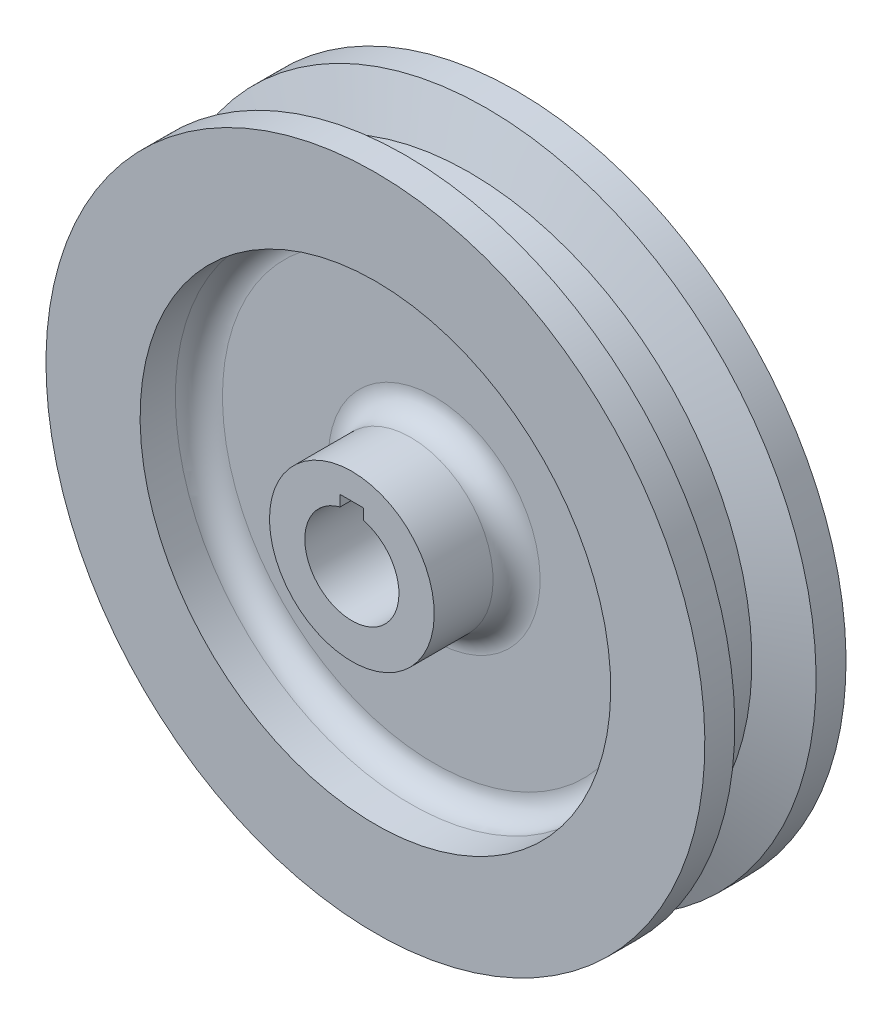
SolidWorks part; units mm, degrees
ref_plane "Front Plane" through (0, 0, 0) normal (0, 0, 1) x (1, 0, 0)
ref_plane "Top Plane" through (0, 0, 0) normal (0, 1, 0) x (1, 0, 0)
ref_plane "Right Plane" through (0, 0, 0) normal (1, 0, 0) x (0, 0, -1)
sketch "Sketch1" plane through (0, 0, 0) normal (1, 0, 0) x (0, 0, -1)
  line L0 (0, 0) -> (0, 58.0259) construction
  line L1 (0, 0) -> (57.8069, 0) construction
  line L2 (9.525, 63.5) -> (19.05, 63.5)
  line L3 (-25.4, 22.225) -> (-9.525, 22.225)
  line L4 (-25.4, 22.225) -> (-25.4, 12.7)
  line L5 (-25.4, 12.7) -> (25.4, 12.7)
  line L6 (25.4, 22.225) -> (25.4, 12.7)
  line L7 (0, 0) -> (-66.8247, 0) construction
  line L9 (-19.05, 88.9) -> (-10.9724, 88.9)
  line L10 (-19.05, 88.9) -> (-19.05, 63.5)
  line L11 (-19.05, 63.5) -> (-9.525, 63.5)
  line L12 (19.05, 88.9) -> (19.05, 63.5)
  line L16 (-3.175, 57.15) -> (-3.175, 28.575)
  line L18 (3.175, 57.15) -> (3.175, 28.575)
  line L19 (9.525, 22.225) -> (25.4, 22.225)
  line L20 (-10.9724, 88.9) -> (-6.35, 76.2)
  line L21 (-6.35, 76.2) -> (6.35, 76.2)
  line L22 (6.35, 76.2) -> (10.9724, 88.9)
  line L23 (10.9724, 88.9) -> (19.05, 88.9)
  arc A0 (-3.175, 28.575) -> (-9.525, 22.225) centre (-9.525, 28.575) cw
  arc A1 (9.525, 22.225) -> (3.175, 28.575) centre (9.525, 28.575) cw
  arc A2 (9.525, 63.5) -> (3.175, 57.15) centre (9.525, 57.15) ccw
  arc A3 (-9.525, 63.5) -> (-3.175, 57.15) centre (-9.525, 57.15) cw
  point P3 (0, 17.4625)
  point P9 (0, 76.2)
  point P29 (3.175, 22.225)
  dimension "D11" = 6.35
  dimension "D1" = 25.4
  dimension "D2" = 44.45
  dimension "D3" = 127
  dimension "D4" = 177.8
  dimension "D5" = 40
  dimension "D6" = 12.7
  dimension "D7" = 38.1
  dimension "D9" = 12.7
  dimension "D10" = 6.35
revolve "Revolve1" add sketch "Sketch1" angle 360 about L7
sketch "Sketch2" plane through (0, 0, 25.4) normal (0, 0, 1) x (1, 0, 0)
  line L1 (-3.175, 15.24) -> (3.175, 15.24)
  line L2 (-3.175, 15.24) -> (-3.175, 0)
  line L3 (-3.175, 0) -> (3.175, 0)
  line L4 (3.175, 15.24) -> (3.175, 0)
  dimension "D1" = 6.35
  dimension "D2" = 15.24
extrude "Cut-Extrude1" cut sketch "Sketch2" against normal through all
